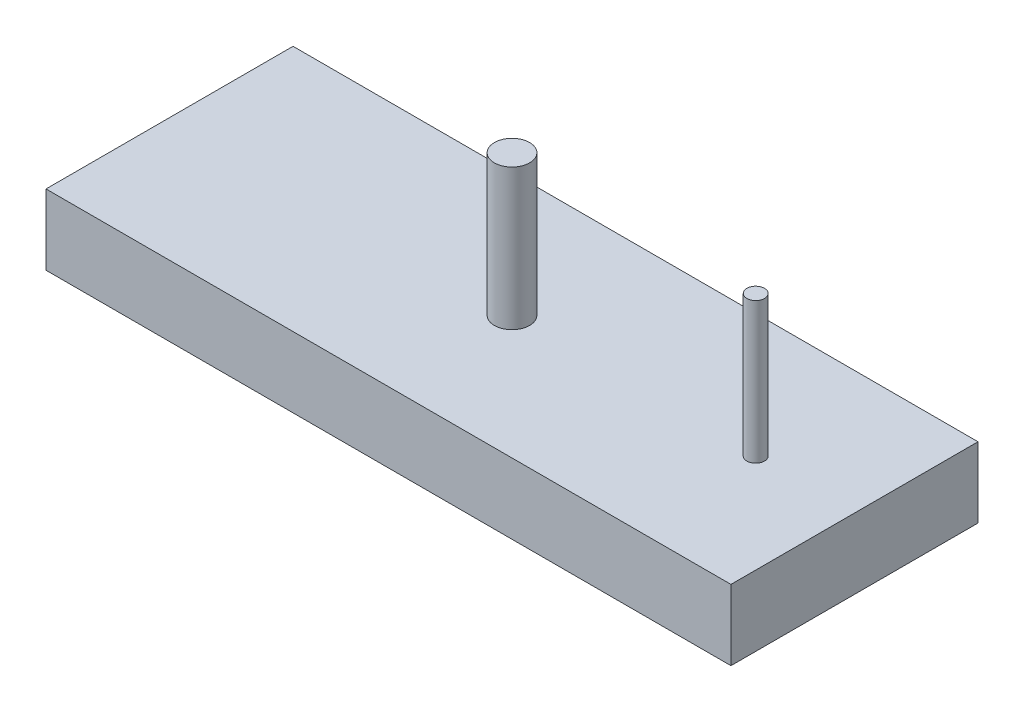
SolidWorks part; units mm, degrees
ref_plane "前基準面" through (0, 0, 0) normal (0, 0, 1) x (1, 0, 0)
ref_plane "上基準面" through (0, 0, 0) normal (0, 1, 0) x (1, 0, 0)
ref_plane "右基準面" through (0, 0, 0) normal (1, 0, 0) x (0, 0, -1)
sketch "草圖1" plane through (0, 0, 0) normal (0, 1, 0) x (1, 0, 0)
  line L1 (-48.6271, 17.5392) -> (48.6271, 17.5392)
  line L2 (-48.6271, 17.5392) -> (-48.6271, -17.5392)
  line L3 (-48.6271, -17.5392) -> (48.6271, -17.5392)
  line L4 (48.6271, 17.5392) -> (48.6271, -17.5392)
  line L5 (-48.6271, 17.5392) -> (48.6271, -17.5392) construction
  line L6 (-48.6271, -17.5392) -> (48.6271, 17.5392) construction
  point P0 (0, 0)
extrude "填料-伸長1" add sketch "草圖1" along normal blind 10
sketch "草圖2" plane through (0, 10, 0) normal (0, 1, 0) x (1, 0, 0)
  circle A0 centre (0, 0) radius 2.5
  circle A1 centre (34.6, 0) radius 1.25
  dimension "D1" = 34.6
  dimension "D2" = 2.5
  dimension "D3" = 5
extrude "填料-伸長2" add sketch "草圖2" along normal blind 20
